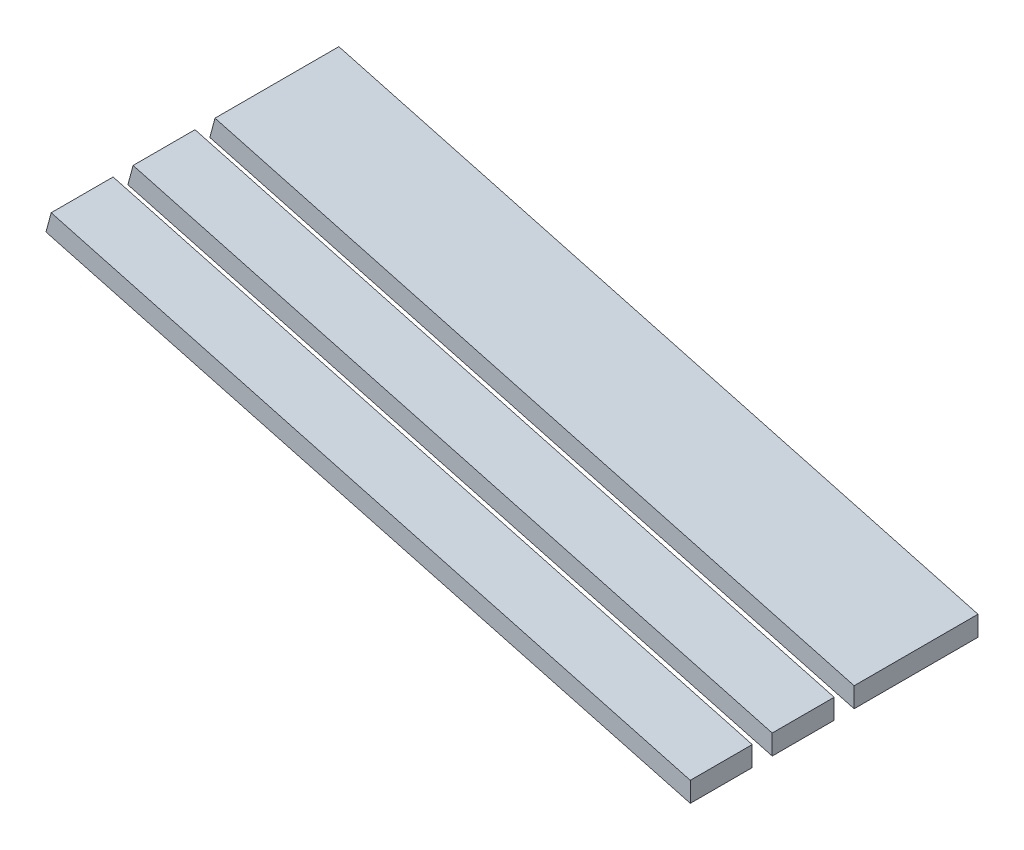
SolidWorks part; units mm, degrees
ref_plane "Front Plane" through (0, 0, 0) normal (0, 0, 1) x (1, 0, 0)
ref_plane "Top Plane" through (0, 0, 0) normal (0, 1, 0) x (1, 0, 0)
ref_plane "Right Plane" through (0, 0, 0) normal (1, 0, 0) x (0, 0, -1)
sketch "Sketch1" plane through (0, 0, 0) normal (0, 1, 0) x (1, 0, 0)
  line L1 (-2150, 875) -> (2150, 875)
  line L2 (-2150, 875) -> (-2150, 255)
  line L3 (-2150, 255) -> (2150, 255)
  line L4 (2150, 875) -> (2150, 255)
  line L5 (-2150, 875) -> (2150, 255) construction
  line L6 (-2150, 255) -> (2150, 875) construction
  line L7 (-2150, 155) -> (2150, 155)
  line L8 (-2150, 155) -> (-2150, -155)
  line L9 (-2150, -155) -> (2150, -155)
  line L10 (2150, 155) -> (2150, -155)
  line L11 (-2150, 155) -> (2150, -155) construction
  line L12 (-2150, -155) -> (2150, 155) construction
  line L13 (-2150, -255) -> (2150, -255)
  line L14 (-2150, -255) -> (-2150, -565)
  line L15 (-2150, -565) -> (2150, -565)
  line L16 (2150, -255) -> (2150, -565)
  line L17 (-2150, -255) -> (2150, -565) construction
  line L18 (-2150, -565) -> (2150, -255) construction
  point P0 (0, 565)
  point P5 (0, 0)
  point P10 (0, -410)
  point P15 (0, 255)
  point P16 (0, -155)
  point P17 (0, -565)
  dimension "D1" = 4300
  dimension "D2" = 310
  dimension "D3" = 310
  dimension "D4" = 620
  dimension "D5" = 100
  dimension "D6" = 100
extrude "Boss-Extrude1" add sketch "Sketch1" along normal blind 100
sketch "Sketch2" plane through (0, 0, 0) normal (0, 0, 1) x (1, 0, 0)
  line L0 (-2150, 100) -> (-2150, 0) construction
  line L1 (-5375, -335.8639) -> (-5375, 864.1361) construction
  line L2 (-2150, 100) -> (-5349.1181, 960.7287)
  line L3 (-5375, 864.1361) -> (-5002.5436, 2254.1623) construction
  line L4 (-5375, 864.1361) -> (-5375, 2098.5159) construction
  line L5 (-5375, 864.1361) -> (-5349.1181, 960.7287)
  line L6 (-5375, 864.1361) -> (-2150, 0)
  line L7 (-2150, 0) -> (-3762.5, 0) construction
  line L8 (-2150, 100) -> (-2150, 0)
  line L9 (-5375, -335.8639) -> (-1776.8624, -335.8639) construction
  dimension "D1" = 3225
  dimension "D2" = 1200
  dimension "D3" = 15
  dimension "D4" = 100
  dimension "D5" = 15
extrude "Boss-Extrude2" add sketch "Sketch2" along normal up to vertex (565 mm away) and the other way up to vertex (875 mm away) up to point (-2150, 100, 565) other way up to point (-2150, 100, -875)
sketch "Sketch3" plane through (0, 100, 0) normal (0, 1, 0) x (1, 0, 0)
  line L0 (-2150, 255) -> (-5875, 255)
  line L1 (-5875, 255) -> (-5875, 155)
  line L2 (-5875, 155) -> (-2150, 155)
  line L3 (-2150, 155) -> (-2150, 255)
  line L4 (-2150, -155) -> (-2150, -255)
  line L5 (-2150, -255) -> (-5875, -255)
  line L6 (-5875, -255) -> (-5875, -155)
  line L7 (-5875, -155) -> (-2150, -155)
  line L8 (-5375, -565) -> (-5375, 875) construction
  dimension "D1" = 500
extrude "Cut-Extrude1" cut sketch "Sketch3" against normal through all both and the other way through all
sketch "Sketch4" plane through (0, 0, 0) normal (0, -1, 0) x (1, 0, 0)
  line L0 (-2150, 565) -> (-2150, 255)
  line L1 (-2150, 255) -> (-2050, 255)
  line L2 (2150, 255) -> (-2150, 255) construction
  line L3 (-2050, 255) -> (-2050, 565)
  line L4 (-2150, 565) -> (2150, 565) construction
  line L5 (-2050, 565) -> (-2150, 565)
  line L6 (-2150, 155) -> (-2150, -155)
  line L7 (-2150, -155) -> (-2050, -155)
  line L8 (2150, -155) -> (-2150, -155) construction
  line L9 (-2050, -155) -> (-2050, 155)
  line L10 (-2150, 155) -> (2150, 155) construction
  line L11 (-2050, 155) -> (-2150, 155)
  line L12 (-2150, -255) -> (-2150, -875)
  line L13 (-2150, -875) -> (-2050, -875)
  line L14 (2150, -875) -> (-2150, -875) construction
  line L15 (-2050, -875) -> (-2050, -255)
  line L16 (-2150, -255) -> (2150, -255) construction
  line L17 (-2050, -255) -> (-2150, -255)
  line L18 (2150, 565) -> (2050, 565)
  line L19 (2050, 565) -> (2050, 255)
  line L20 (2050, 255) -> (2150, 255)
  line L21 (2150, 255) -> (2150, 565)
  line L22 (2150, 155) -> (2150, -155)
  line L23 (2150, -155) -> (2050, -155)
  line L24 (2050, -155) -> (2050, 155)
  line L25 (2050, 155) -> (2150, 155)
  line L26 (2150, -255) -> (2150, -875)
  line L27 (2150, -875) -> (2050, -875)
  line L28 (2050, -875) -> (2050, -255)
  line L29 (2050, -255) -> (2150, -255)
  dimension "D1" = 100
  dimension "D2" = 100
extrude "Boss-Extrude3" add sketch "Sketch4" along normal up to surface (347.0178 mm away)
sketch "Sketch5" plane through (0, 100, 0) normal (0, 1, 0) x (1, 0, 0)
  line L0 (2150, 875) -> (2150, -565)
  line L1 (-2150, 875) -> (-2150, -565)
  line L3 (-2150, -565) -> (2150, -565)
  line L4 (-2150, 875) -> (2150, 875)
extrude "Cut-Extrude2" cut sketch "Sketch5" against normal blind 1771
